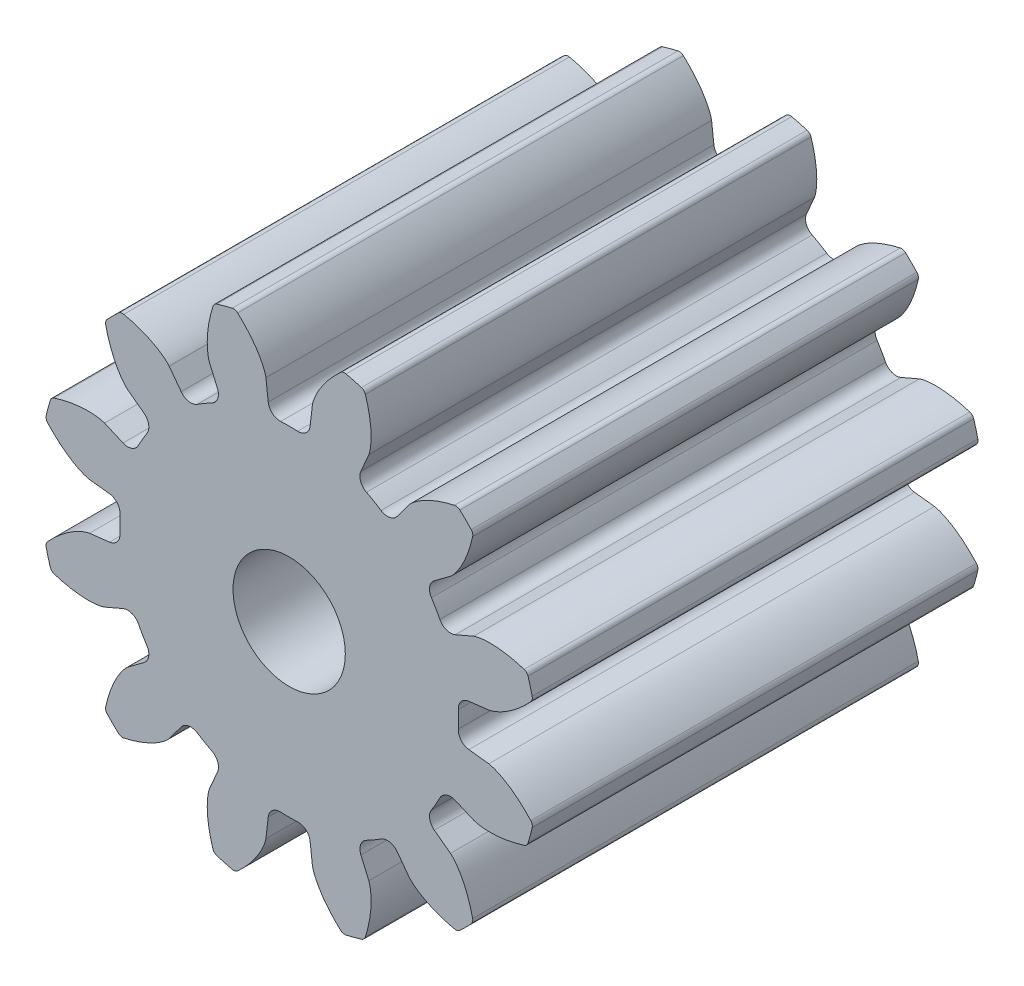
SolidWorks part; units mm, degrees
material "ABS"
ref_plane "Front" through (0, 0, 0) normal (0, 0, 1) x (1, 0, 0)
ref_plane "Top" through (0, 0, 0) normal (0, 1, 0) x (1, 0, 0)
ref_plane "Right" through (0, 0, 0) normal (1, 0, 0) x (0, 0, -1)
sketch "Sketch1" plane through (0, 0, 0) normal (0, 0, 1) x (1, 0, 0)
  circle A0 centre (0, 0) radius 7.112
extrude "Boss-Extrude1" add sketch "Sketch1" along normal blind 12.7
sketch "Sketch3" plane through (0, 0, 0) normal (0, 0, 1) x (1, 0, 0)
  line L0 (0, 0) -> (43.7181, 0) construction
  line L2 (0, 0) -> (-0.5585, 4.7936) construction
  line L3 (0, 0) -> (0.5585, 4.7936) construction
  line L4 (0.5585, 4.7936) -> (0.663, 5.6899) construction
  line L5 (0, 0) -> (0, 61.276) construction
  line L6 (-0.5585, 4.7936) -> (-0.663, 5.6899) construction
  circle A0 centre (0, 0) radius 7.112 construction
  circle A1 centre (0, 0) radius 6.096 construction
  circle A2 centre (0, 0) radius 5.7284 construction
  arc A3 (0.5585, 4.7936) -> (-0.5585, 4.7936) centre (0, 0) ccw construction
  arc A5 (1.5343, 6.9445) -> (-1.5343, 6.9445) centre (0, 0) ccw
  spline S0 degree 4 poles (-0.663, 5.6899) (-0.6633, 5.6921) (-0.6642, 5.6985) (-0.6665, 5.7105) (-0.6707, 5.7299) (-0.677, 5.7545) (-0.6862, 5.786) (-0.6984, 5.8228) (-0.7131, 5.863) (-0.7305, 5.9063) (-0.7492, 5.949) (-0.769, 5.9913) (-0.7899, 6.0331) (-0.8163, 6.0832) (-0.8498, 6.1427) (-0.8914, 6.2112) (-0.9415, 6.2877) (-0.9956, 6.3642) (-1.0514, 6.4384) (-1.1105, 6.5119) (-1.1698, 6.582) (-1.2341, 6.6532) (-1.295, 6.7182) (-1.3662, 6.7892) (-1.4246, 6.8459) (-1.5048, 6.9188) (-1.5531, 6.9612) (-1.6108, 7.0102) (-1.6369, 7.0315) (-1.653, 7.0447) knots 0 0 0 0 0 0.005377 0.015084 0.028532 0.04661 0.064855 0.092111 0.119476 0.146842 0.174209 0.201575 0.228941 0.256307 0.307035 0.361767 0.4165 0.471232 0.525964 0.580697 0.635429 0.690161 0.744894 0.799626 0.854358 0.909091 0.954545 1 1 1 1 1 construction
  spline S1 degree 4 poles (-0.663, 5.6899) (-0.6633, 5.6921) (-0.6642, 5.6985) (-0.6665, 5.7105) (-0.6707, 5.7299) (-0.677, 5.7545) (-0.6862, 5.786) (-0.6984, 5.8228) (-0.7131, 5.863) (-0.7305, 5.9063) (-0.7492, 5.949) (-0.769, 5.9913) (-0.7899, 6.0331) (-0.8163, 6.0832) (-0.8498, 6.1427) (-0.8914, 6.2112) (-0.9415, 6.2877) (-0.9956, 6.3642) (-1.0514, 6.4384) (-1.1105, 6.5119) (-1.1698, 6.582) (-1.2341, 6.6532) (-1.295, 6.7182) (-1.3662, 6.7892) (-1.4246, 6.8459) (-1.4874, 6.903) (-1.5184, 6.9305) (-1.5343, 6.9445) knots 0 0 0 0 0 0.005377 0.015084 0.028532 0.04661 0.064855 0.092111 0.119476 0.146842 0.174209 0.201575 0.228941 0.256307 0.307035 0.361767 0.4165 0.471232 0.525964 0.580697 0.635429 0.690161 0.744894 0.799626 0.854358 0.909091 0.909091 0.909091 0.909091 0.909091
  spline S2 degree 4 poles (0.663, 5.6899) (0.6633, 5.6921) (0.6642, 5.6985) (0.6665, 5.7105) (0.6707, 5.7299) (0.677, 5.7545) (0.6862, 5.786) (0.6984, 5.8228) (0.7131, 5.863) (0.7305, 5.9063) (0.7492, 5.949) (0.769, 5.9913) (0.7899, 6.0331) (0.8163, 6.0832) (0.8498, 6.1427) (0.8914, 6.2112) (0.9415, 6.2877) (0.9956, 6.3642) (1.0514, 6.4384) (1.1105, 6.5119) (1.1698, 6.582) (1.2341, 6.6532) (1.295, 6.7182) (1.3662, 6.7892) (1.4246, 6.8459) (1.5048, 6.9188) (1.5531, 6.9612) (1.6108, 7.0102) (1.6369, 7.0315) (1.653, 7.0447) knots 0 0 0 0 0 0.005377 0.015084 0.028532 0.04661 0.064855 0.092111 0.119476 0.146842 0.174209 0.201575 0.228941 0.256307 0.307035 0.361767 0.4165 0.471232 0.525964 0.580697 0.635429 0.690161 0.744894 0.799626 0.854358 0.909091 0.954545 1 1 1 1 1 construction
  spline S3 degree 4 poles (0.663, 5.6899) (0.6633, 5.6921) (0.6642, 5.6985) (0.6665, 5.7105) (0.6707, 5.7299) (0.677, 5.7545) (0.6862, 5.786) (0.6984, 5.8228) (0.7131, 5.863) (0.7305, 5.9063) (0.7492, 5.949) (0.769, 5.9913) (0.7899, 6.0331) (0.8163, 6.0832) (0.8498, 6.1427) (0.8914, 6.2112) (0.9415, 6.2877) (0.9956, 6.3642) (1.0514, 6.4384) (1.1105, 6.5119) (1.1698, 6.582) (1.2341, 6.6532) (1.295, 6.7182) (1.3662, 6.7892) (1.4246, 6.8459) (1.4874, 6.903) (1.5184, 6.9305) (1.5343, 6.9445) knots 0 0 0 0 0 0.005377 0.015084 0.028532 0.04661 0.064855 0.092111 0.119476 0.146842 0.174209 0.201575 0.228941 0.256307 0.307035 0.361767 0.4165 0.471232 0.525964 0.580697 0.635429 0.690161 0.744894 0.799626 0.854358 0.909091 0.909091 0.909091 0.909091 0.909091
  point P0 (0, 4.826)
sketch "DCLTBC" plane through (0, 0, 0) normal (0, 0, 1) x (1, 0, 0)
  line L0 (0, 0) -> (41.04, 0) construction
  line L1 (-0.5585, 4.7936) -> (-0.663, 5.6899) construction
  line L2 (0.5585, 4.7936) -> (0.663, 5.6899) construction
  line L3 (-0.5585, 4.7936) -> (-0.663, 5.6899)
  line L4 (0.5585, 4.7936) -> (0.663, 5.6899)
  line L5 (0, 0) -> (0, 104.9356) construction
  circle A0 centre (0, 0) radius 7.112
  circle A1 centre (0, 0) radius 6.096 construction
  circle A2 centre (0, 0) radius 5.7284 construction
  arc A3 (0.5585, 4.7936) -> (-0.5585, 4.7936) centre (0, 0) ccw construction
  arc A4 (0.5585, 4.7936) -> (-0.5585, 4.7936) centre (0, 0) ccw
  spline S0 degree 4 poles (-992.1977, -123.9559) (-11.5747, 3.5606) (-0.7537, 5.116) (-0.6074, 5.4411) (-0.6707, 5.7299) (-0.677, 5.7545) (-0.6862, 5.786) (-0.6984, 5.8228) (-0.7131, 5.863) (-0.7305, 5.9063) (-0.7492, 5.949) (-0.769, 5.9913) (-0.7899, 6.0331) (-0.8163, 6.0832) (-0.8498, 6.1427) (-0.8914, 6.2112) (-0.9415, 6.2877) (-0.9956, 6.3642) (-1.0514, 6.4384) (-1.1105, 6.5119) (-1.1698, 6.582) (-1.2341, 6.6532) (-1.295, 6.7182) (-1.3662, 6.7892) (-1.6953, 7.109) (-2.9906, 8.162) (15.8911, -8.5109) (-754.212, 665.3283) knots -0.646533 -0.646533 -0.646533 -0.646533 -0.646533 0.005377 0.015084 0.028532 0.04661 0.064855 0.092111 0.119476 0.146842 0.174209 0.201575 0.228941 0.256307 0.307035 0.361767 0.4165 0.471232 0.525964 0.580697 0.635429 0.690161 0.744894 0.799626 0.854358 1.923834 1.923834 1.923834 1.923834 1.923834 only from (-0.663, 5.6899) to (-1.5343, 6.9445) construction
  spline S1 degree 4 poles (992.1977, -123.9559) (11.5747, 3.5606) (0.7537, 5.116) (0.6074, 5.4411) (0.6707, 5.7299) (0.677, 5.7545) (0.6862, 5.786) (0.6984, 5.8228) (0.7131, 5.863) (0.7305, 5.9063) (0.7492, 5.949) (0.769, 5.9913) (0.7899, 6.0331) (0.8163, 6.0832) (0.8498, 6.1427) (0.8914, 6.2112) (0.9415, 6.2877) (0.9956, 6.3642) (1.0514, 6.4384) (1.1105, 6.5119) (1.1698, 6.582) (1.2341, 6.6532) (1.295, 6.7182) (1.3662, 6.7892) (1.6953, 7.109) (2.9906, 8.162) (-15.8911, -8.5109) (754.212, 665.3283) knots -0.646533 -0.646533 -0.646533 -0.646533 -0.646533 0.005377 0.015084 0.028532 0.04661 0.064855 0.092111 0.119476 0.146842 0.174209 0.201575 0.228941 0.256307 0.307035 0.361767 0.4165 0.471232 0.525964 0.580697 0.635429 0.690161 0.744894 0.799626 0.854358 1.923834 1.923834 1.923834 1.923834 1.923834 only from (0.663, 5.6899) to (1.5343, 6.9445) construction
  spline S2 degree 4 poles (-0.663, 5.6899) (-0.6633, 5.6921) (-0.6642, 5.6985) (-0.6665, 5.7105) (-0.6707, 5.7299) (-0.677, 5.7545) (-0.6862, 5.786) (-0.6984, 5.8228) (-0.7131, 5.863) (-0.7305, 5.9063) (-0.7492, 5.949) (-0.769, 5.9913) (-0.7899, 6.0331) (-0.8163, 6.0832) (-0.8498, 6.1427) (-0.8914, 6.2112) (-0.9415, 6.2877) (-0.9956, 6.3642) (-1.0514, 6.4384) (-1.1105, 6.5119) (-1.1698, 6.582) (-1.2341, 6.6532) (-1.295, 6.7182) (-1.3662, 6.7892) (-1.4246, 6.8459) (-1.4874, 6.903) (-1.5184, 6.9305) (-1.5343, 6.9445) knots 0 0 0 0 0 0.005377 0.015084 0.028532 0.04661 0.064855 0.092111 0.119476 0.146842 0.174209 0.201575 0.228941 0.256307 0.307035 0.361767 0.4165 0.471232 0.525964 0.580697 0.635429 0.690161 0.744894 0.799626 0.854358 0.909091 0.909091 0.909091 0.909091 0.909091
  spline S3 degree 4 poles (0.663, 5.6899) (0.6633, 5.6921) (0.6642, 5.6985) (0.6665, 5.7105) (0.6707, 5.7299) (0.677, 5.7545) (0.6862, 5.786) (0.6984, 5.8228) (0.7131, 5.863) (0.7305, 5.9063) (0.7492, 5.949) (0.769, 5.9913) (0.7899, 6.0331) (0.8163, 6.0832) (0.8498, 6.1427) (0.8914, 6.2112) (0.9415, 6.2877) (0.9956, 6.3642) (1.0514, 6.4384) (1.1105, 6.5119) (1.1698, 6.582) (1.2341, 6.6532) (1.295, 6.7182) (1.3662, 6.7892) (1.4246, 6.8459) (1.4874, 6.903) (1.5184, 6.9305) (1.5343, 6.9445) knots 0 0 0 0 0 0.005377 0.015084 0.028532 0.04661 0.064855 0.092111 0.119476 0.146842 0.174209 0.201575 0.228941 0.256307 0.307035 0.361767 0.4165 0.471232 0.525964 0.580697 0.635429 0.690161 0.744894 0.799626 0.854358 0.909091 0.909091 0.909091 0.909091 0.909091
extrude "Cut-Extrude-DCLTBC" cut sketch "DCLTBC" along normal through all
fillet "Fillet-Tip-DCLTBC" radius 0.1704 2 edges at (1.5343, 6.9445, 6.35) (-1.5343, 6.9445, 6.35)
fillet "Fillet-Root-DCLTBC" radius 0.3409 2 edges at (-0.5585, 4.7936, 6.35) (0.5585, 4.7936, 6.35)
pattern_circular "CirPattern-DCLTBC" count 12 over 360 about axis through (0, 0, 12.7) along (0, 0, 1) of "Cut-Extrude-DCLTBC", "Fillet-Tip-DCLTBC", "Fillet-Root-DCLTBC"
sketch "DCGTBC" [suppressed] plane through (0, 0, 0) normal (0, 0, 1) x (1, 0, 0)
  line L0 (0, 0) -> (41.04, 0) construction
  line L1 (-22.6634, 1.9828) -> (0, 0) construction
  line L2 (0, 0) -> (22.6634, 1.9828) construction
  line L3 (0, 0) -> (-16.5124, 0)
  line L5 (0, 0) -> (0, 104.9356) construction
  circle A0 centre (0, 0) radius 25
  circle A1 centre (0, 0) radius 24 construction
  circle A2 centre (0, 0) radius 21.7514 construction
  arc A3 (0.0626, 22.7499) -> (-0.0626, 22.7499) centre (0, 0) ccw construction
  arc A11 (22.6634, 1.9828) -> (-22.6634, 1.9828) centre (0, 0) ccw
  spline S4 degree 4 poles (999.7589, -2.0808) (12.8658, 20.0937) (0.2547, 20.6746) (0.0189, 21.2606) (0.0654, 21.8429) (0.0715, 21.8997) (0.0812, 21.973) (0.095, 22.0592) (0.1126, 22.1539) (0.1343, 22.2566) (0.1583, 22.3589) (0.1845, 22.4607) (0.2124, 22.562) (0.2486, 22.6844) (0.2952, 22.8308) (0.3543, 23.0013) (0.4268, 23.1939) (0.5065, 23.3893) (0.5897, 23.5809) (0.6793, 23.7735) (0.7698, 23.9592) (0.8695, 24.151) (0.9643, 24.3275) (1.0767, 24.524) (1.517, 25.277) (3.0654, 27.5692) (-13.787, 0.9944) (540.7091, 867.0187) knots -0.561807 -0.561807 -0.561807 -0.561807 -0.561807 0.005377 0.015084 0.028532 0.04661 0.064855 0.092111 0.119476 0.146842 0.174209 0.201575 0.228941 0.256307 0.307035 0.361767 0.4165 0.471232 0.525964 0.580697 0.635429 0.690161 0.744894 0.799626 0.854358 1.731906 1.731906 1.731906 1.731906 1.731906 only from (0.0598, 21.7513) to (1.3455, 24.9638) construction
  spline S5 degree 4 poles (-999.7589, -2.0808) (-12.8658, 20.0937) (-0.2547, 20.6746) (-0.0189, 21.2606) (-0.0654, 21.8429) (-0.0715, 21.8997) (-0.0812, 21.973) (-0.095, 22.0592) (-0.1126, 22.1539) (-0.1343, 22.2566) (-0.1583, 22.3589) (-0.1845, 22.4607) (-0.2124, 22.562) (-0.2486, 22.6844) (-0.2952, 22.8308) (-0.3543, 23.0013) (-0.4268, 23.1939) (-0.5065, 23.3893) (-0.5897, 23.5809) (-0.6793, 23.7735) (-0.7698, 23.9592) (-0.8695, 24.151) (-0.9643, 24.3275) (-1.0767, 24.524) (-1.517, 25.277) (-3.0654, 27.5692) (13.787, 0.9944) (-540.7091, 867.0187) knots -0.561807 -0.561807 -0.561807 -0.561807 -0.561807 0.005377 0.015084 0.028532 0.04661 0.064855 0.092111 0.119476 0.146842 0.174209 0.201575 0.228941 0.256307 0.307035 0.361767 0.4165 0.471232 0.525964 0.580697 0.635429 0.690161 0.744894 0.799626 0.854358 1.731906 1.731906 1.731906 1.731906 1.731906 only from (-0.0598, 21.7513) to (-1.3455, 24.9638) construction
  spline S6 degree 4 poles (0.0598, 21.7513) (0.0599, 21.7565) (0.0603, 21.7709) (0.0618, 21.7983) (0.0654, 21.8429) (0.0715, 21.8997) (0.0812, 21.973) (0.095, 22.0592) (0.1126, 22.1539) (0.1343, 22.2566) (0.1583, 22.3589) (0.1845, 22.4607) (0.2124, 22.562) (0.2486, 22.6844) (0.2952, 22.8308) (0.3543, 23.0013) (0.4268, 23.1939) (0.5065, 23.3893) (0.5897, 23.5809) (0.6793, 23.7735) (0.7698, 23.9592) (0.8695, 24.151) (0.9643, 24.3275) (1.0767, 24.524) (1.1693, 24.6823) (1.27, 24.8447) (1.3197, 24.9235) (1.3455, 24.9638) knots 0 0 0 0 0 0.005377 0.015084 0.028532 0.04661 0.064855 0.092111 0.119476 0.146842 0.174209 0.201575 0.228941 0.256307 0.307035 0.361767 0.4165 0.471232 0.525964 0.580697 0.635429 0.690161 0.744894 0.799626 0.854358 0.909091 0.909091 0.909091 0.909091 0.909091
  spline S7 degree 4 poles (-0.0598, 21.7513) (-0.0599, 21.7565) (-0.0603, 21.7709) (-0.0618, 21.7983) (-0.0654, 21.8429) (-0.0715, 21.8997) (-0.0812, 21.973) (-0.095, 22.0592) (-0.1126, 22.1539) (-0.1343, 22.2566) (-0.1583, 22.3589) (-0.1845, 22.4607) (-0.2124, 22.562) (-0.2486, 22.6844) (-0.2952, 22.8308) (-0.3543, 23.0013) (-0.4268, 23.1939) (-0.5065, 23.3893) (-0.5897, 23.5809) (-0.6793, 23.7735) (-0.7698, 23.9592) (-0.8695, 24.151) (-0.9643, 24.3275) (-1.0767, 24.524) (-1.1693, 24.6823) (-1.27, 24.8447) (-1.3197, 24.9235) (-1.3455, 24.9638) knots 0 0 0 0 0 0.005377 0.015084 0.028532 0.04661 0.064855 0.092111 0.119476 0.146842 0.174209 0.201575 0.228941 0.256307 0.307035 0.361767 0.4165 0.471232 0.525964 0.580697 0.635429 0.690161 0.744894 0.799626 0.854358 0.909091 0.909091 0.909091 0.909091 0.909091
  dimension "D1" = 5
  dimension "D2" = 5
extrude "Cut-Extrude-DCGTBC" [suppressed] cut sketch "DCGTBC" along normal through all
fillet "Fillet-Tip-DCGTBC" [suppressed] radius 0.1704
pattern_circular "CirPattern-DCGTBC" [suppressed] count 12 over 360
sketch "Sketch4" plane through (0, 0, 12.7) normal (0, 0, 1) x (1, 0, 0)
  line L1 (-1.9169, 1.9965) -> (1.9169, 1.9965)
  line L2 (-1.9169, 1.9965) -> (-1.9169, -1.9965)
  line L3 (-1.9169, -1.9965) -> (1.9169, -1.9965)
  line L4 (1.9169, 1.9965) -> (1.9169, -1.9965)
  line L5 (-1.9169, 1.9965) -> (1.9169, -1.9965) construction
  line L6 (-1.9169, -1.9965) -> (1.9169, 1.9965) construction
  circle A0 centre (0, 0) radius 2.7678
  dimension "D1" = 5.5356
  dimension "D2" = 3.8338
extrude "Cut-Extrude1" cut sketch "Sketch4" against normal through all contours L4 L1 L2 L3 | L3 A0 | L1 A0
sketch "Sketch6" plane through (0, 0, 12.7) normal (0, 0, 1) x (1, 0, 0)
  line L0 (1.9169, 1.9965) -> (1.9169, -1.9965) construction
  line L1 (-1.9169, 1.9965) -> (-1.9169, -1.9965) construction
  line L2 (1.9169, 1.9965) -> (1.9169, -1.9965)
  line L3 (-1.9169, 1.9965) -> (-1.9169, -1.9965)
  circle A0 centre (0, 0) radius 1.6
  arc A1 (1.9169, 1.9965) -> (-1.9169, 1.9965) centre (0, 0) ccw construction
  arc A2 (-1.9169, -1.9965) -> (1.9169, -1.9965) centre (0, 0) ccw construction
  arc A3 (1.9169, 1.9965) -> (-1.9169, 1.9965) centre (0, 0) ccw
  arc A4 (-1.9169, -1.9965) -> (1.9169, -1.9965) centre (0, 0) ccw
  dimension "D1" = 3.2
extrude "Boss-Extrude2" add sketch "Sketch6" against normal blind 4.826
chamfer "Chamfer1" distance 0.508 angle 45 4 edges at (0, 2.7678, 0) (0, -2.7678, 0) (-1.9169, 0, 0) (1.9169, 0, 0)
equation "\"DiametralPitch\"= 25'Diametral Pitch"
equation "\"NumTeeth\"= 12'Number of Teeth"
equation "\"PressureAngle\"= 20deg'Pressure Angle"
equation "\"Addendum\"= 1 / \"DiametralPitch\"'Addendum"
equation "\"Dedendum\"= 1.25 / \"DiametralPitch\"'Dedendum"
equation "\"WorkingDepth\"= 2 / \"DiametralPitch\"'Working Depth - here for REF (Not used in building model)"
equation "\"WholeDepth\"= 2.25 / \"DiametralPitch\"'Whole Depth - here for REF (Not used in building model)"
equation "\"Clearance\"= .25 / \"DiametralPitch\"'Clearance"
equation "\"CircularPitch\"= pi / \"DiametralPitch\"'Circular Pitch - here for REF (Not used in building model)"
equation "\"PitchCircle\"= \"NumTeeth\" / \"DiametralPitch\"'Pitch Circle - or - Pitch Diameter"
equation "\"OutsideDiameter\"= ( \"NumTeeth\" + 2 ) / \"DiametralPitch\"'Outside Diameter"
equation "\"Fillet_Root\"= \"Clearance\" * cos ( \"PressureAngle\" ) * tan ( ( 90 + \"PressureAngle\" ) / 2 ) 'Fillet Root"
equation "\"AddendumCircle\"= \"PitchCircle\" + ( 2 * \"Addendum\" )'Addendum Circle - or - Addendum Diameter"
equation "\"DedendumCircle\"= \"PitchCircle\" - ( 2 * \"Dedendum\" )'Dedendum Circle - or - Dedendum Diameter"
equation "\"BaseCircle\"= \"PitchCircle\" * cos ( \"PressureAngle\" )'Base Circle - Base Diameter"
equation "\"PitchAngle\"= 360deg / \"NumTeeth\"'Pitch Angle"
equation "\"Alpha\"= sqr ( \"PitchCircle\" ^ 2 - \"BaseCircle\" ^ 2 ) / \"BaseCircle\" * 180 / PI - \"PressureAngle\"'Alpha - Used for Calculating Beta"
equation "\"Beta\"= ( \"PitchAngle\" / 4 - ( \"Alpha\" - 90 ) )'Beta - Used in definition of the parameters for the parametric equation driven curve"
equation "\"Gamma\"= ( \"PitchAngle\" / 4 - ( \"Alpha\" + 90 ) )'Gamma - Used in definition of the parameters for the parametric equation driven curve"
equation "\"Phi\"= sqr ( ( \"AddendumCircle\" / 2 ) ^ 2 - ( \"BaseCircle\" / 2 ) ^ 2 ) / ( \"BaseCircle\" / 2 )'Phi - Used in definition of the parameters for the parametric equation driven curve"
equation "\"DCGTBC\"= iif ( \"DedendumCircle\" > \"BaseCircle\" , \"unsuppressed\" , \"suppressed\" )'if Dedendum Circle IS GREATER THAN BaseCircle THEN UnsuppressORSuppress FEATURE"
equation "\"DCLTBC\"= iif ( \"DedendumCircle\" - .002 > \"BaseCircle\" , \"suppressed\" , \"unsuppressed\" )'if Dedendum Circle - .002 IS GREATER THAN BaseCircle THEN SuppressORUnsuppress FEATURE"
equation "\"Cut-Extrude-DCGTBC\"= iif ( \"DedendumCircle\" > \"BaseCircle\" , \"unsuppressed\" , \"suppressed\" )'if Dedendum Circle IS GREATER THAN BaseCircle THEN UnsuppressORSuppress FEATURE"
equation "\"Cut-Extrude-DCLTBC\"= iif ( \"DedendumCircle\" - .002 > \"BaseCircle\" , \"suppressed\" , \"unsuppressed\" )'if Dedendum Circle - .002 IS GREATER THAN BaseCircle THEN SuppressORUnsuppress FEATURE"
equation "\"CirPattern-DCGTBC\"= iif ( \"DedendumCircle\" > \"BaseCircle\" , \"unsuppressed\" , \"suppressed\" )'if Dedendum Circle IS GREATER THAN BaseCircle THEN UnsuppressORSuppress FEATURE"
equation "\"CirPattern-DCLTBC\"= iif ( \"DedendumCircle\" - .002 > \"BaseCircle\" , \"suppressed\" , \"unsuppressed\" )'if Dedendum Circle - .002 IS GREATER THAN BaseCircle THEN SuppressORUnsuppress FEATURE"
equation "\"Fillet-Tip-DCGTBC\"= iif ( \"DedendumCircle\" > \"BaseCircle\" , \"unsuppressed\" , \"suppressed\" )'if Dedendum Circle IS GREATER THAN BaseCircle THEN UnsuppressORSuppress FEATURE"
equation "\"Fillet-Tip-DCLTBC\"= iif ( \"DedendumCircle\" - .002 > \"BaseCircle\" , \"suppressed\" , \"unsuppressed\" )'if Dedendum Circle - .002 IS GREATER THAN BaseCircle THEN SuppressORUnsuppress FEATURE"
equation "\"Fillet-Root-DCLTBC\"= iif ( \"DedendumCircle\" - .002 > \"BaseCircle\" , \"suppressed\" , \"unsuppressed\" )'if Dedendum Circle - .002 IS GREATER THAN BaseCircle THEN SuppressORUnsuppress FEATURE"
equation "\"D1@CirPattern-DCGTBC\"= \"NumTeeth\"'Number of Teeth"
equation "\"D1@CirPattern-DCLTBC\"= \"NumTeeth\"'Number of Teeth"
equation "\"D1@Fillet-Tip-DCGTBC\"= \"Fillet_Root\" / 2 'Tip Rad For Large No of Teeth"
equation "\"D1@Fillet-Tip-DCLTBC\"=\"Fillet_Root\" / 2'Tip Rad For Small No of Teeth"
equation "\"D1@Fillet-Root-DCLTBC\"= \"Fillet_Root\"'Fillet Root"
